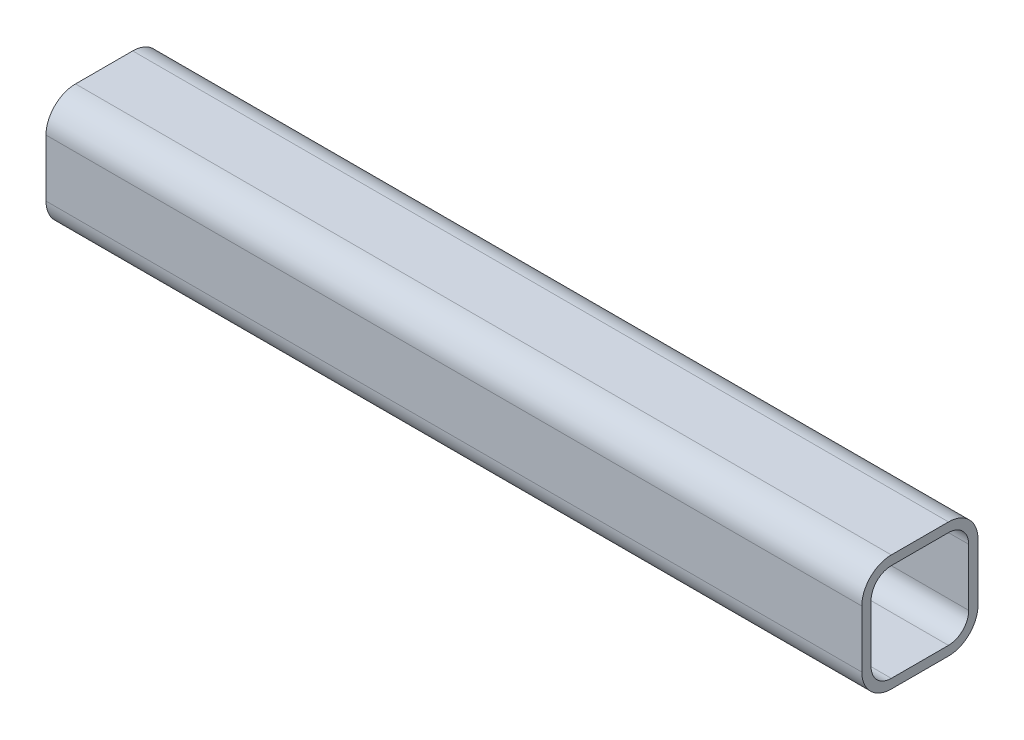
SolidWorks part; units mm, degrees
material "AISI 1015 Acero estirado en frío (SS)"
ref_plane "Alzado" through (0, 0, 0) normal (0, 0, 1) x (1, 0, 0)
ref_plane "Planta" through (0, 0, 0) normal (0, 1, 0) x (1, 0, 0)
ref_plane "Vista lateral" through (0, 0, 0) normal (1, 0, 0) x (0, 0, -1)
sketch "Croquis1" plane through (0, 0, 0) normal (0, 0, 1) x (1, 0, 0)
  line L0 (-178.3088, 0) -> (172.6912, 0)
  dimension "D1" = 351
other "Miembro estructural1"
ref_plane "Plano1" through (-178.3088, 0, 0) normal (1, 0, 0) x (0, 1, 0)
sketch "Sketch1" plane through (-178.3088, 0, 0) normal (1, 0, 0) x (0, 1, 0)
  line L0 (-12.3, -21) -> (12.3, -21)
  line L1 (-21, -12.3) -> (-21, 12.3)
  line L2 (12.3, 21) -> (-12.3, 21)
  line L3 (21, 12.3) -> (21, -12.3)
  line L4 (-12.3, -25) -> (12.3, -25)
  line L5 (-25, -12.3) -> (-25, 12.3)
  line L6 (12.3, 25) -> (-12.3, 25)
  line L7 (25, 12.3) -> (25, -12.3)
  line L8 (0, 0) -> (21, 0) construction
  line L9 (0, 0) -> (0, 21) construction
  arc A0 (25, 12.3) -> (12.3, 25) centre (12.3, 12.3) ccw
  arc A1 (12.3, -25) -> (25, -12.3) centre (12.3, -12.3) ccw
  arc A2 (-25, -12.3) -> (-12.3, -25) centre (-12.3, -12.3) ccw
  arc A3 (-12.3, 25) -> (-25, 12.3) centre (-12.3, 12.3) ccw
  arc A4 (-12.3, 21) -> (-21, 12.3) centre (-12.3, 12.3) ccw
  arc A5 (21, 12.3) -> (12.3, 21) centre (12.3, 12.3) ccw
  arc A6 (12.3, -21) -> (21, -12.3) centre (12.3, -12.3) ccw
  arc A7 (-21, -12.3) -> (-12.3, -21) centre (-12.3, -12.3) ccw
  point P3 (0, 25)
  point P4 (25, 0)
  point P5 (0, -25)
  point P6 (-25, 0)
  point P7 (-25, 25)
  point P8 (-25, -25)
  point P33 (0, 0)
  point P35 (25, -25)
  point P36 (25, 25)
  point P37 (0, 0)
  dimension "D1" = 12.7
  dimension "Thickness" = 4
  dimension "V_leg" = 50
